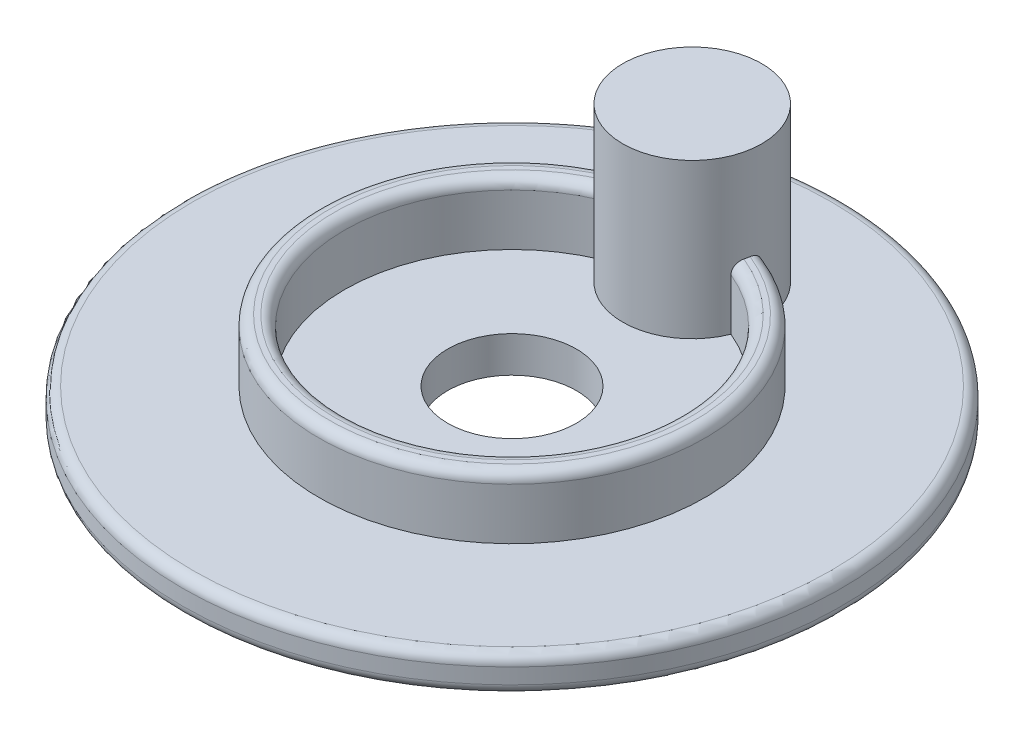
SolidWorks part; units mm, degrees
ref_plane "Front" through (0, 0, 0) normal (0, 0, 1) x (1, 0, 0)
ref_plane "Top" through (0, 0, 0) normal (0, 1, 0) x (1, 0, 0)
ref_plane "Right" through (0, 0, 0) normal (1, 0, 0) x (0, 0, -1)
sketch "Sketch1" plane through (0, 0, 0) normal (0, 1, 0) x (1, 0, 0)
  circle A0 centre (0, 0) radius 64
  dimension "D1" = 128
extrude "Boss-Extrude1" add sketch "Sketch1" along normal blind 7
sketch "Sketch2" plane through (0, 7, 0) normal (0, 1, 0) x (1, 0, 0)
  circle A0 centre (0, 0) radius 37.5
  circle A2 centre (0, 0) radius 32.5
  dimension "D1" = 75
  dimension "D2" = 5
extrude "Boss-Extrude2" add sketch "Sketch2" along normal blind 12 contours A0 | A2
sketch "Sketch3" plane through (0, 7, 0) normal (0, 1, 0) x (1, 0, 0)
  circle A0 centre (0, 0) radius 12.5
  dimension "D1" = 25
extrude "Cut-Extrude1" cut sketch "Sketch3" against normal through all contours A0
fillet "Fillet1" radius 2 4 edges at (0, 19, 32.5) (0, 19, 37.5) (0, 0, 64) (0, 7, 64)
sketch "Sketch4" plane through (0, 7, 0) normal (0, 1, 0) x (1, 0, 0)
  line L0 (0, 0) -> (0, 35) construction
  circle A0 centre (0, 35) radius 13.5
  dimension "D1" = 27
  dimension "D2" = 35
extrude "Boss-Extrude3" add sketch "Sketch4" along normal blind 30
sketch "Sketch5" plane through (0, 37, 0) normal (0, 1, 0) x (1, 0, 0)
  circle A0 centre (0, 35) radius 6.9079
